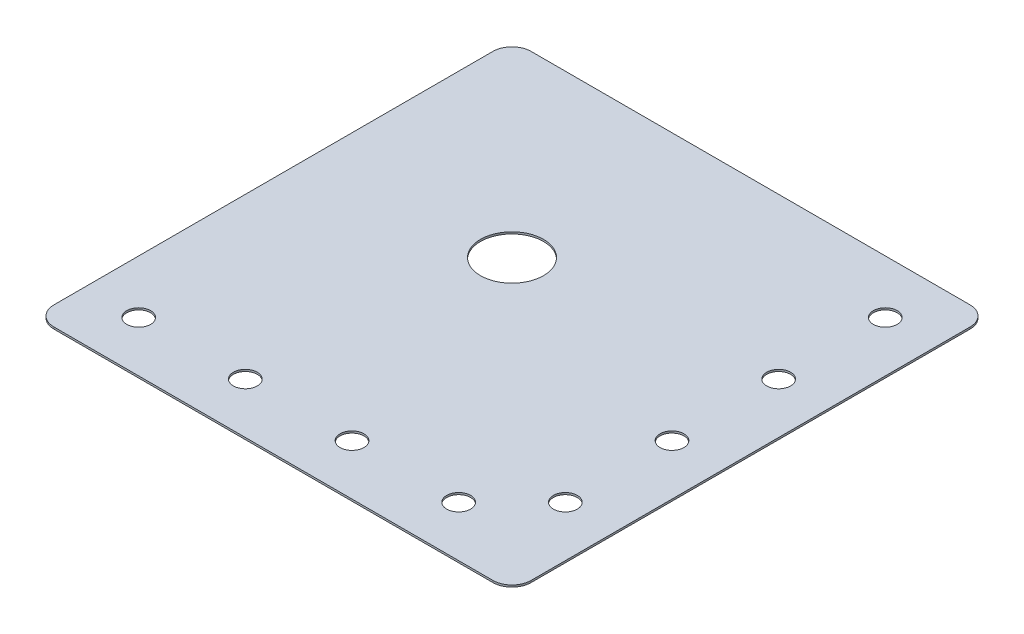
SolidWorks part; units mm, degrees
ref_plane "Front Plane" through (0, 0, 0) normal (0, 0, 1) x (1, 0, 0)
ref_plane "Top Plane" through (0, 0, 0) normal (0, 1, 0) x (1, 0, 0)
ref_plane "Right Plane" through (0, 0, 0) normal (1, 0, 0) x (0, 0, -1)
sketch "Sketch1" plane through (0, 0, 0) normal (0, 1, 0) x (1, 0, 0)
  line L0 (-37.3672, 42.925) -> (-37.3672, -3.075)
  line L1 (-35.3672, -5.075) -> (10.6328, -5.075)
  line L2 (12.6328, -3.075) -> (12.6328, 42.925)
  line L3 (10.6328, 44.925) -> (-35.3672, 44.925)
  circle A0 centre (-17.6672, 25.225) radius 3.3
  arc A1 (-37.3672, -3.075) -> (-35.3672, -5.075) centre (-35.3672, -3.075) ccw
  arc A2 (10.6328, -5.075) -> (12.6328, -3.075) centre (10.6328, -3.075) ccw
  arc A3 (12.6328, 42.925) -> (10.6328, 44.925) centre (10.6328, 42.925) ccw
  arc A4 (-35.3672, 44.925) -> (-37.3672, 42.925) centre (-35.3672, 42.925) ccw
  circle A5 centre (7.3328, 16.9875) radius 1.25
  circle A6 centre (7.3328, 28.1625) radius 1.25
  circle A7 centre (7.3328, 39.3375) radius 1.25
  circle A8 centre (7.3328, 5.8125) radius 1.25
  circle A9 centre (1.7453, 0.225) radius 1.25
  circle A10 centre (-9.4297, 0.225) radius 1.25
  circle A11 centre (-20.6047, 0.225) radius 1.25
  circle A12 centre (-31.7797, 0.225) radius 1.25
extrude "Boss-Extrude1" add sketch "Sketch1" along normal blind 0.2
